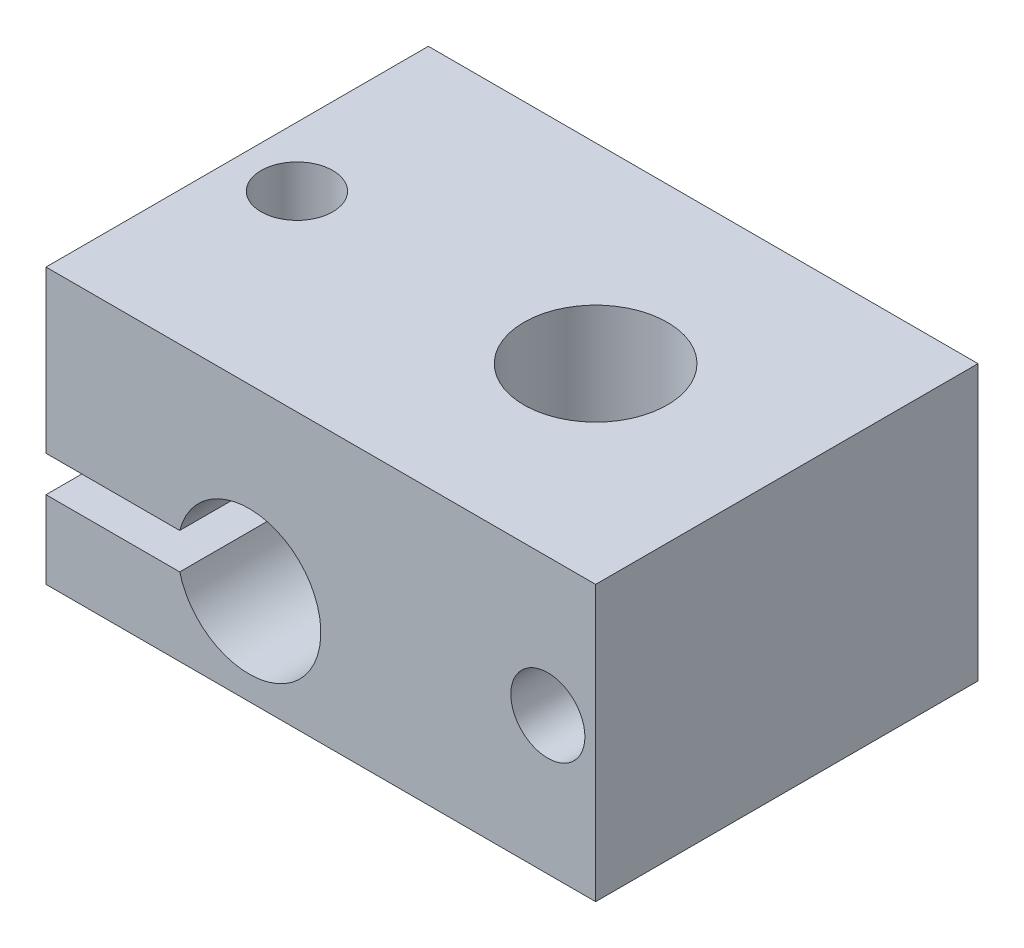
SolidWorks part; units mm, degrees
ref_plane "前视基准面" through (0, 0, 0) normal (0, 0, 1) x (1, 0, 0)
ref_plane "上视基准面" through (0, 0, 0) normal (0, 1, 0) x (1, 0, 0)
ref_plane "右视基准面" through (0, 0, 0) normal (1, 0, 0) x (0, 0, -1)
sketch "草图1" plane through (0, 0, 0) normal (0, 0, 1) x (1, 0, 0)
  line L0 (-3.414, -0.8168) -> (-8.7965, -0.8168) construction
  line L1 (14.2035, 6.6832) -> (-8.7965, 6.6832)
  line L2 (14.2035, 6.6832) -> (14.2035, -4.8168)
  line L3 (14.2035, -4.8168) -> (-8.7965, -4.8168)
  line L4 (-8.7965, 6.6832) -> (-8.7965, -0.0668)
  line L5 (-3.2012, -0.0668) -> (-8.7965, -0.0668)
  line L6 (-3.2012, -1.5668) -> (-8.7965, -1.5668)
  line L7 (-8.7965, -1.5668) -> (-8.7965, -4.8168)
  arc A0 (-3.2012, -1.5668) -> (-3.2012, -0.0668) centre (-0.2965, -0.8168) ccw
  circle A1 centre (12.2035, 0.9332) radius 1.55
  point P0 (0, 0)
  dimension "D4" = 6
  dimension "D7" = 3.1
  dimension "D1" = 14.5
  dimension "D2" = 23
  dimension "D3" = 4
  dimension "D5" = 2
  dimension "D6" = 5.75
  dimension "D8" = 11.5
  dimension "D9" = 1.5
extrude "凸台-拉伸2" add sketch "草图1" along normal blind 16
sketch "草图2" plane through (0, 6.6832, 0) normal (0, 1, 0) x (1, 0, 0)
  line L0 (14.2035, -16) -> (-8.7965, -16) construction
  line L1 (14.2035, -16) -> (14.2035, 0) construction
  circle A0 centre (-6.2965, -8) radius 1.5
  circle A1 centre (6.2035, -8) radius 3
  dimension "D1" = 3
  dimension "D3" = 6
  dimension "D4" = 8
  dimension "D6" = 8
  dimension "D7" = 20.5
extrude "切除-拉伸1" cut sketch "草图2" against normal through all
sketch "草图3" plane through (0, -4.8168, 0) normal (0, -1, 0) x (1, 0, 0)
  line L0 (14.2035, 16) -> (14.2035, 0) construction
  circle A0 centre (12.2035, 8) radius 1.5
  point P0 (6.2035, 8)
  dimension "D1" = 2
extrude "切除-拉伸2" cut sketch "草图3" against normal blind 4
